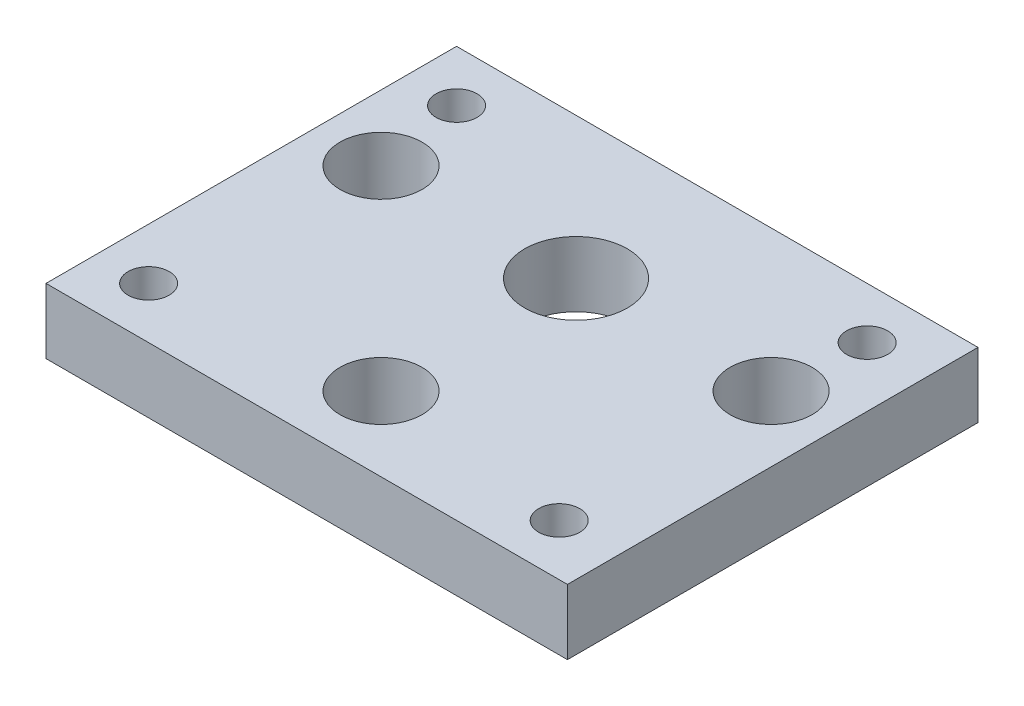
SolidWorks part; units mm, degrees
ref_plane "Alzado" through (0, 0, 0) normal (0, 0, 1) x (1, 0, 0)
ref_plane "Planta" through (0, 0, 0) normal (0, 1, 0) x (1, 0, 0)
ref_plane "Vista lateral" through (0, 0, 0) normal (1, 0, 0) x (0, 0, -1)
sketch "Croquis1" plane through (0, 0, 0) normal (0, 1, 0) x (1, 0, 0)
  line L1 (-25.4, 40) -> (25.4, 40)
  line L2 (-25.4, 40) -> (-25.4, -40)
  line L3 (-25.4, -40) -> (25.4, -40)
  line L4 (25.4, 40) -> (25.4, -40)
  line L5 (-25.4, 40) -> (25.4, -40) construction
  line L6 (-25.4, -40) -> (25.4, 40) construction
  point P0 (0, 0)
  dimension "D1" = 80
  dimension "D2" = 50.8
extrude "Saliente-Extruir1" add sketch "Croquis1" along normal blind 6.35
sketch "Croquis4" plane through (0, 6.35, 0) normal (0, 1, 0) x (1, 0, 0)
  circle A0 centre (-19, 19.4661) radius 4
  circle A1 centre (19, 19.4661) radius 4
  circle A2 centre (0, 0.4661) radius 4
  dimension "D3" = 8
  dimension "D5" = 8
  dimension "D4" = 8
  dimension "D1" = 38
  dimension "D2" = 19
  dimension "D6" = 19
extrude "Cortar-Extruir3" cut sketch "Croquis4" against normal through all
sketch "Croquis5" plane through (0, 6.35, 0) normal (0, 1, 0) x (1, 0, 0)
  line L0 (25.4, -40) -> (25.4, 40) construction
  line L1 (-25.4, -40) -> (25.4, -40)
  line L2 (-25.4, -40) -> (-25.4, -27.3)
  line L3 (-25.4, -27.3) -> (25.4, -27.3)
  line L4 (25.4, -40) -> (25.4, -27.3)
  dimension "D1" = 12.7
extrude "Cortar-Extruir4" cut sketch "Croquis5" against normal through all
sketch "Croquis6" plane through (0, 6.35, 0) normal (0, 1, 0) x (1, 0, 0)
  line L0 (25.4, -27.3) -> (25.4, 40) construction
  line L1 (-25.4, -27.3) -> (25.4, -27.3)
  line L2 (-25.4, -27.3) -> (-25.4, -6.7734)
  line L3 (-25.4, -6.7734) -> (25.4, -6.7734)
  line L4 (25.4, -27.3) -> (25.4, -6.7734)
extrude "Cortar-Extruir5" cut sketch "Croquis6" against normal blind 10
sketch "Croquis7" plane through (0, 0, 0) normal (0, -1, 0) x (1, 0, 0)
  line L0 (25.4, 6.7734) -> (25.4, -40) construction
  line L1 (-25.4, 6.7734) -> (25.4, 6.7734)
  line L2 (-25.4, 6.7734) -> (-25.4, -33.2266)
  line L3 (-25.4, -33.2266) -> (25.4, -33.2266)
  line L4 (25.4, 6.7734) -> (25.4, -33.2266)
  line L6 (-25.4, -33.2266) -> (25.4, -33.2266)
  line L7 (-25.4, -33.2266) -> (-25.4, -40)
  line L8 (-25.4, -40) -> (25.4, -40)
  line L9 (25.4, -33.2266) -> (25.4, -40)
  line M5 (25.4, -40) -> (25.4, 6.7734)
  line M7 (-25.4, 6.7734) -> (-25.4, -40)
  line M8 (-25.4, -40) -> (25.4, -40)
  dimension "D1" = 40
extrude "Cortar-Extruir6" cut sketch "Croquis7" against normal blind 10 contours L3 M7 M8 M5
sketch "Croquis9" plane through (0, 0, 0) normal (0, -1, 0) x (1, 0, 0)
  line L0 (-19, -19.4661) -> (19, -19.4661) construction
  circle A0 centre (0, -19.4661) radius 5
  dimension "D1" = 10
extrude "Cortar-Extruir7" cut sketch "Croquis9" against normal blind 10
sketch "Croquis10" plane through (0, 0, 0) normal (0, -1, 0) x (1, 0, 0)
  line L0 (25.4, 6.7734) -> (-25.4, 6.7734) construction
  line L1 (-25.4, -33.2266) -> (-25.4, 6.7734) construction
  circle A0 centre (-20.4, 1.7734) radius 2
  circle A1 centre (19.6, 1.7734) radius 2
  circle A2 centre (19.6, -28.2266) radius 2
  circle A3 centre (-20.4, -28.2266) radius 2
  dimension "D1" = 4
  dimension "D2" = 5
  dimension "D3" = 5
  dimension "D4" = 2
  dimension "D5" = 2
extrude "Cortar-Extruir8" cut sketch "Croquis10" against normal blind 10
equation "\"D2@Croquis4\"=\"D1@Croquis4\"/2"
equation "\"D5@Croquis4\"=\"D3@Croquis4\""
equation "\"D4@Croquis4\"=\"D3@Croquis4\""
